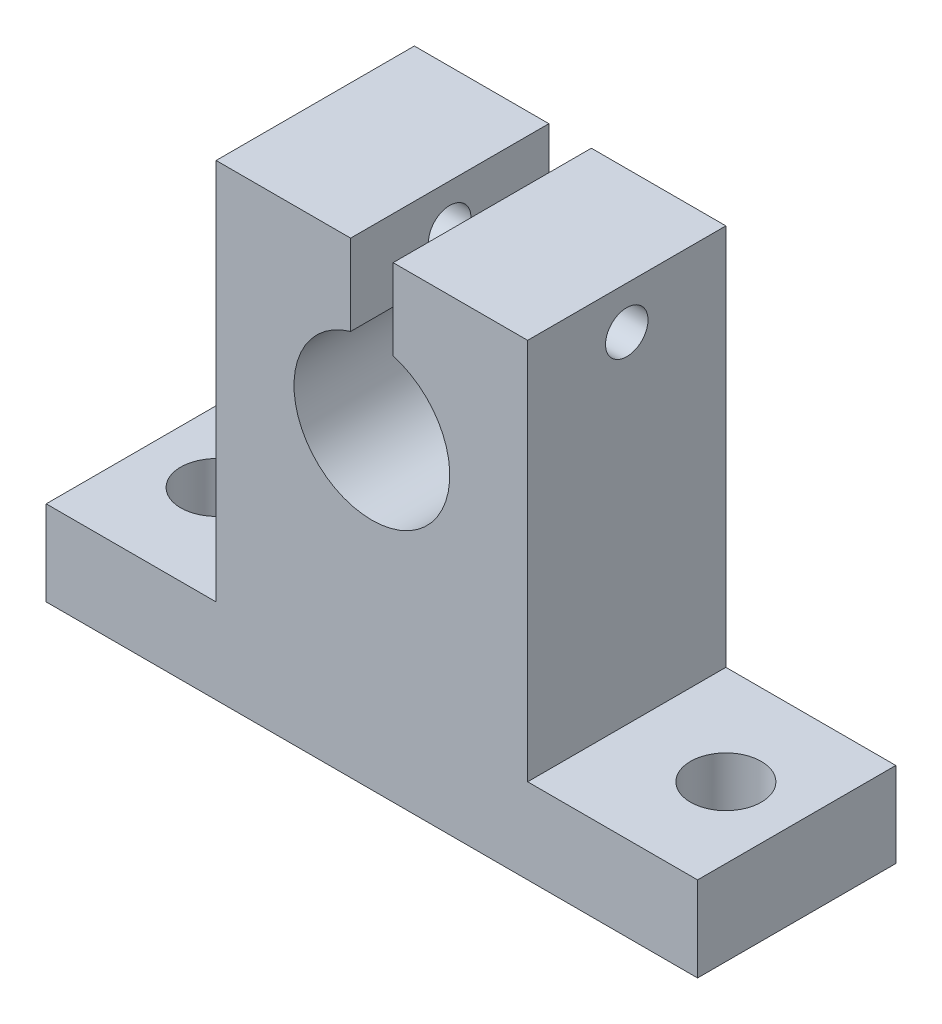
SolidWorks part; units mm, degrees
ref_plane "前视基准面" through (0, 0, 0) normal (0, 0, 1) x (1, 0, 0)
ref_plane "上视基准面" through (0, 0, 0) normal (0, 1, 0) x (1, 0, 0)
ref_plane "右视基准面" through (0, 0, 0) normal (1, 0, 0) x (0, 0, -1)
sketch "草图1" plane through (0, 0, 0) normal (0, 0, 1) x (1, 0, 0)
  line L0 (-0.7265, -16.25) -> (-0.7265, 5.75) construction
  line L1 (-11.7265, 16.75) -> (10.2735, 16.75)
  line L2 (-11.7265, 16.75) -> (-11.7265, -16.25)
  line L3 (-11.7265, -16.25) -> (10.2735, -16.25)
  line L4 (10.2735, 16.75) -> (10.2735, -16.25)
  line L5 (-0.7265, 16.75) -> (-0.7265, -16.25) construction
  line L6 (10.2735, -16.25) -> (22.2735, -16.25)
  line L7 (10.2735, -16.25) -> (10.2735, -10.25)
  line L8 (10.2735, -10.25) -> (22.2735, -10.25)
  line L9 (22.2735, -16.25) -> (22.2735, -10.25)
  line L10 (-11.7265, -10.25) -> (-23.7265, -10.25)
  line L11 (-23.7265, -16.25) -> (-23.7265, -10.25)
  line L12 (-11.7265, -16.25) -> (-23.7265, -16.25)
  line L13 (-11.7265, -16.25) -> (-11.7265, -10.25)
  line L15 (-2.2265, 25.4361) -> (0.7735, 25.4361)
  line L16 (-2.2265, 25.4361) -> (-2.2265, 8.0639)
  line L17 (-2.2265, 8.0639) -> (0.7735, 8.0639)
  line L18 (0.7735, 25.4361) -> (0.7735, 8.0639)
  line L19 (-2.2265, 25.4361) -> (0.7735, 8.0639) construction
  line L20 (-2.2265, 8.0639) -> (0.7735, 25.4361) construction
  circle A0 centre (-0.7265, 5.75) radius 4.5
  dimension "D4" = 12
  dimension "D1" = 22
  dimension "D2" = 33
  dimension "D3" = 22
  dimension "D5" = 6
  dimension "D6" = 3
extrude "凸台-拉伸1" add sketch "草图1" along normal blind 14 contours A0 L16 L1 L2 L3 L4 L18 | L6 L9 L8 L4 | L12 L2 L10 L11
sketch "草图2" plane through (0, -16.25, 0) normal (0, -1, 0) x (-1, 0, 0)
  line L0 (23.7265, -7) -> (18.7265, -7) construction
  line L1 (23.7265, -14) -> (23.7265, 0) construction
  line L2 (0.7265, -14) -> (0.7265, 0) construction
  line L3 (23.7265, -14) -> (-22.2735, -14) construction
  line L4 (23.7265, 0) -> (-22.2735, 0) construction
  circle A0 centre (18.7265, -7) radius 2.5
  circle A1 centre (-17.2735, -7) radius 2.5
  dimension "D1" = 5
extrude "切除-拉伸1" cut sketch "草图2" against normal blind 14
ref_plane "基准面4" through (-2.2265, 9.9926, 14) normal (0, -1, 0) x (-1, 0, 0)
sketch "草图4" plane through (-11.7265, 0, 0) normal (-1, 0, 0) x (0, 0, 1)
  line L0 (7, 16.75) -> (7, 13.75) construction
  line L1 (14, 16.75) -> (0, 16.75) construction
  circle A0 centre (7, 13.75) radius 1.5
  dimension "D1" = 3
extrude "切除-拉伸2" cut sketch "草图4" against normal blind 28
sketch "草图5" plane through (0, 0, 14) normal (0, 0, 1) x (1, 0, 0)
  line L0 (3.7735, 5.75) -> (-5.2265, 5.75) construction
  arc A0 (-2.2265, 9.9926) -> (0.7735, 9.9926) centre (-0.7265, 5.75) ccw construction
  circle A1 centre (-0.7265, 5.75) radius 5.5
extrude "切除-拉伸3" cut sketch "草图5" against normal blind 22
